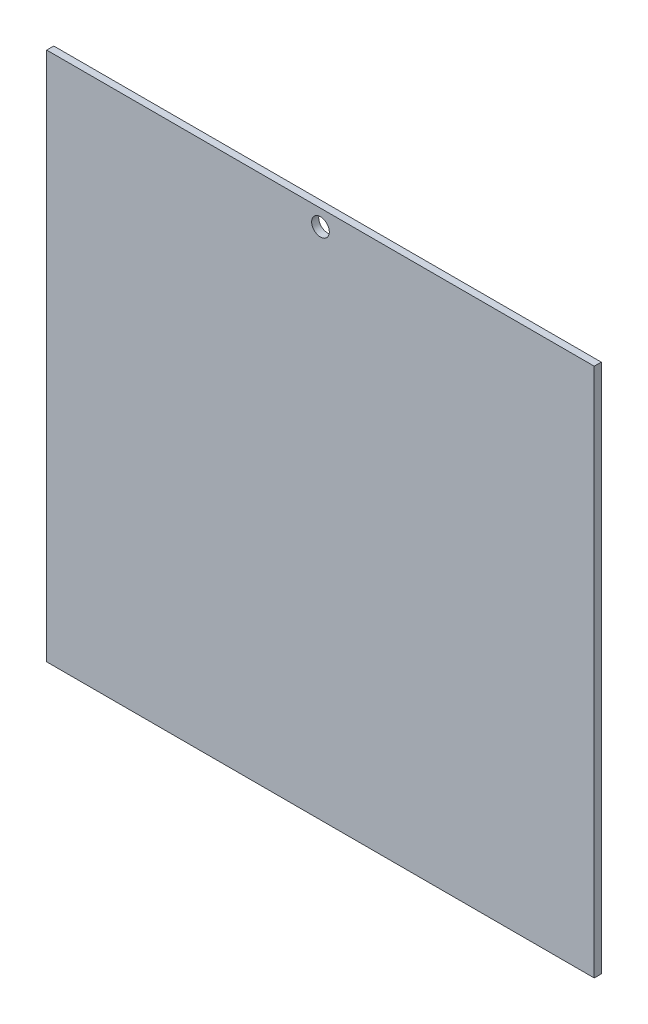
SolidWorks part; units mm, degrees
material "Oak"
ref_plane "Front Plane" through (0, 0, 0) normal (0, 0, 1) x (1, 0, 0)
ref_plane "Top Plane" through (0, 0, 0) normal (0, 1, 0) x (1, 0, 0)
ref_plane "Right Plane" through (0, 0, 0) normal (1, 0, 0) x (0, 0, -1)
sketch "Sketch1" plane through (0, 0, 0) normal (0, 0, 1) x (1, 0, 0)
  line L1 (-155, 150) -> (155, 150)
  line L2 (-155, 150) -> (-155, -150)
  line L3 (-155, -150) -> (155, -150)
  line L4 (155, 150) -> (155, -150)
  line L5 (-155, 150) -> (155, -150) construction
  line L6 (-155, -150) -> (155, 150) construction
  point P0 (0, 0)
  dimension "D1" = 310
  dimension "D2" = 300
extrude "Boss-Extrude1" add sketch "Sketch1" along normal blind 4
sketch "Sketch2" plane through (0, 0, 4) normal (0, 0, 1) x (1, 0, 0)
  circle A0 centre (0, 140.812) radius 5
extrude "Cut-Extrude1" cut sketch "Sketch2" against normal blind 10
